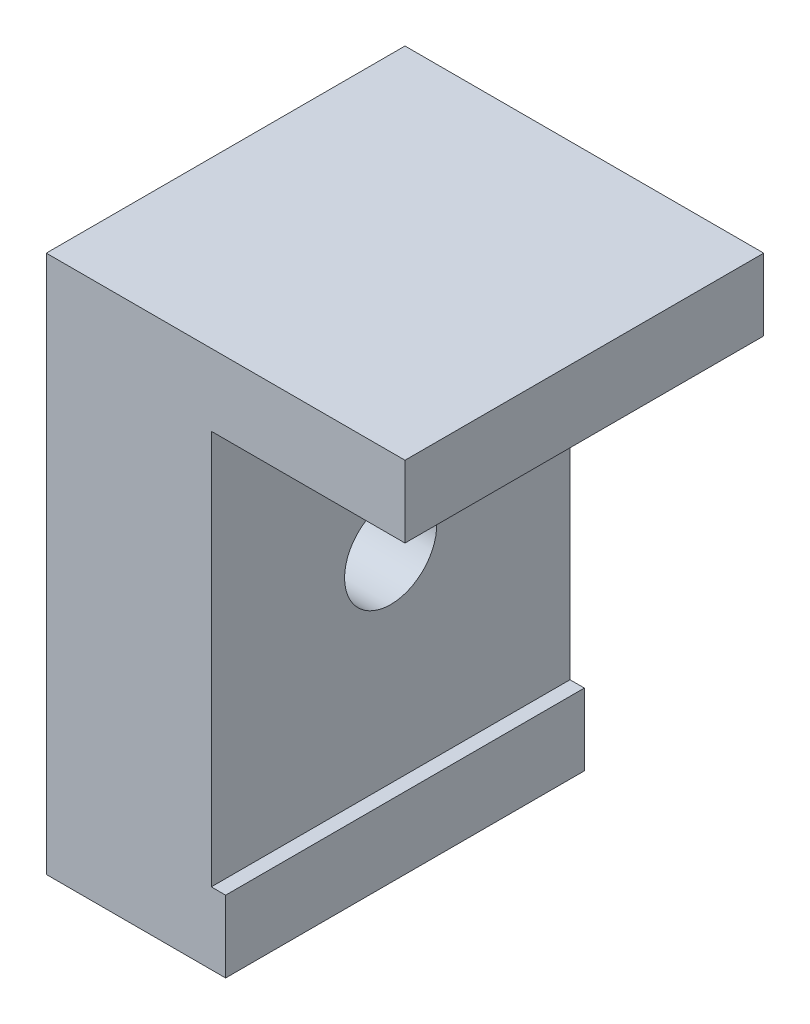
SolidWorks part; units mm, degrees
material "6061 Alloy"
ref_plane "Front Plane" through (0, 0, 0) normal (0, 0, 1) x (1, 0, 0)
ref_plane "Top Plane" through (0, 0, 0) normal (0, 1, 0) x (1, 0, 0)
ref_plane "Right Plane" through (0, 0, 0) normal (1, 0, 0) x (0, 0, -1)
sketch "Sketch1" plane through (0, 0, 0) normal (1, 0, 0) x (0, 0, -1)
  line L1 (-6.35, -9.525) -> (6.35, -9.525)
  line L2 (-6.35, -9.525) -> (-6.35, 9.525)
  line L3 (-6.35, 9.525) -> (6.35, 9.525)
  line L4 (6.35, -9.525) -> (6.35, 9.525)
  line L5 (-6.35, -9.525) -> (6.35, 9.525) construction
  line L6 (-6.35, 9.525) -> (6.35, -9.525) construction
  point P0 (0, 0)
  dimension "D1" = 12.7
  dimension "D2" = 19.05
extrude "Boss-Extrude1" add sketch "Sketch1" along normal blind 12.7
sketch "Sketch2" plane through (0, 0, 6.35) normal (0, 0, 1) x (1, 0, 0)
  line L1 (12.7, -9.525) -> (6.35, -9.525)
  line L2 (12.7, -9.525) -> (12.7, 6.985)
  line L3 (12.7, 6.985) -> (6.35, 6.985)
  line L4 (6.35, -9.525) -> (6.35, 6.985)
  dimension "D1" = 6.35
  dimension "D2" = 16.51
extrude "Cut-Extrude1" cut sketch "Sketch2" against normal through all
sketch "Sketch3" plane through (0, 0, 6.35) normal (0, 0, 1) x (1, 0, 0)
  line L0 (6.35, 6.985) -> (6.35, -9.525) construction
  line L1 (6.35, -6.985) -> (5.842, -6.985)
  line L2 (6.35, -6.985) -> (6.35, 6.985)
  line L3 (6.35, 6.985) -> (5.842, 6.985)
  line L4 (5.842, -6.985) -> (5.842, 6.985)
  line L5 (12.7, 6.985) -> (6.35, 6.985) construction
  point P8 (6.096, -6.985)
  dimension "D1" = 13.97
  dimension "D2" = 0
  dimension "D3" = 0.254
extrude "Cut-Extrude2" cut sketch "Sketch3" against normal through all
hole_wizard "#4 Clearance Hole1" positions "Sketch4" profile "Sketch5" hole size "#4" standard "ANSI Inch" end condition through all
sketch "Sketch4" plane through (0, 0, 0) normal (-1, 0, 0) x (0, 0, 1)
  line L0 (6.35, -9.525) -> (-6.35, -9.525) construction
  point P0 (0, 0.127)
  dimension "D1" = 9.652
sketch "Sketch5" plane through (0, 0.127, 0) normal (0, 1, 0) x (0, 0, 1)
  line L0 (0, 0) -> (0, 12.7)
  line L1 (0, 12.7) -> (1.6319, 12.7)
  line L2 (1.6319, 12.7) -> (1.6319, 0)
  line L5 (1.6319, 0) -> (0, 0)
  line L11 (0, -6.35) -> (0, 107.95) construction
  dimension "Thru Hole Dia." = 3.2639
  dimension "Thru Hole Depth" = 12.7
